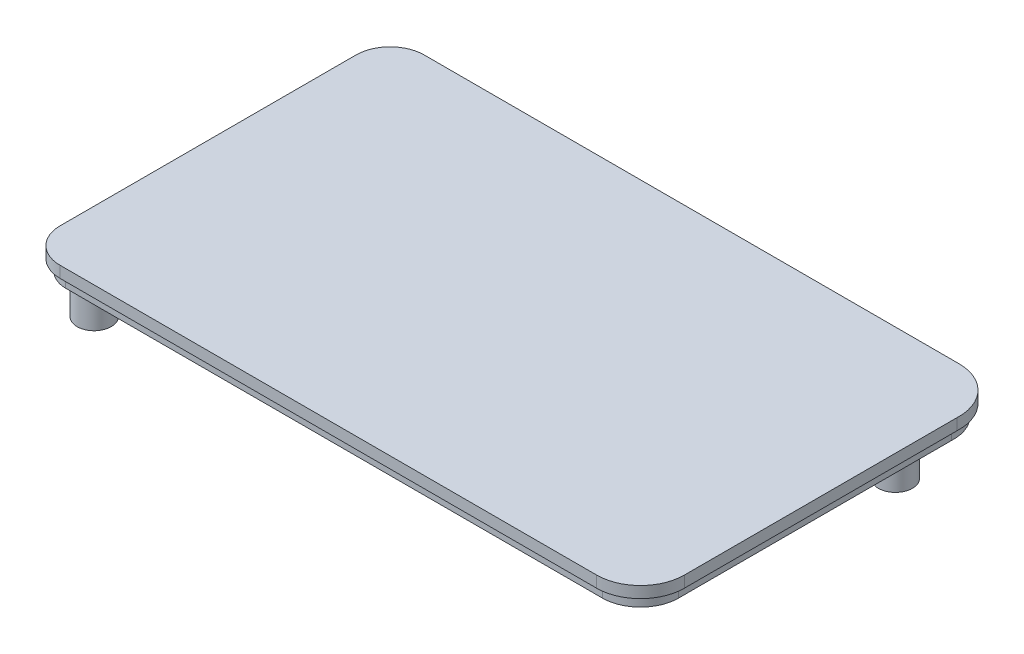
SolidWorks part; units mm, degrees
ref_plane "Front" through (0, 0, 0) normal (0, 0, 1) x (1, 0, 0)
ref_plane "Top" through (0, 0, 0) normal (0, 1, 0) x (1, 0, 0)
ref_plane "Right" through (0, 0, 0) normal (1, 0, 0) x (0, 0, -1)
sketch "Çizim1" plane through (0, 0, 0) normal (0, 1, 0) x (1, 0, 0)
  line L0 (69.3543, 0) -> (22.2059, 0)
  line L9 (19.2052, 3.0007) -> (19.2052, 28.9993)
  line L10 (22.2059, 32) -> (69.2041, 32)
  line L11 (73.204, 27.8016) -> (73.2052, 3.8497)
  arc A0 (19.2052, 28.9993) -> (22.2059, 32) centre (22.2059, 28.9993) cw
  arc A1 (73.204, 27.8016) -> (69.2041, 32) centre (69.2041, 27.9954) ccw
  arc A2 (19.2052, 3.0007) -> (22.2059, 0) centre (22.2059, 3.0007) ccw
  arc A3 (69.3543, 0) -> (73.2052, 3.8497) centre (69.3543, 3.8509) ccw
extrude "Yükseklik-Ekstrüzyon1" add sketch "Çizim1" along normal blind 2
sketch "Çizim2" plane through (0, 0, 0) normal (0, -1, 0) x (1, 0, 0)
  line L0 (22.2059, -0.5) -> (69.3543, -0.5)
  line L1 (72.7052, -3.8498) -> (72.7046, -27.8258)
  line L2 (69.2041, -31.5) -> (22.2059, -31.5)
  line L3 (19.7052, -28.9993) -> (19.7052, -3.0007)
  line L4 (22.2059, 0) -> (69.3543, 0)
  line L5 (73.2052, -3.8498) -> (73.2046, -27.8141)
  line L6 (69.2041, -32) -> (22.2059, -32)
  line L7 (19.2052, -28.9993) -> (19.2052, -3.0007)
  arc A0 (19.7052, -3.0007) -> (22.2059, -0.5) centre (22.2059, -3.0007) cw
  arc A1 (19.7052, -28.9993) -> (22.2059, -31.5) centre (22.2059, -28.9993) ccw
  arc A2 (69.2041, -31.5) -> (72.7046, -27.8258) centre (69.2041, -27.9954) ccw
  arc A3 (72.7052, -3.8498) -> (69.3543, -0.5) centre (69.3543, -3.8509) ccw
  arc A4 (72.7052, -3.8498) -> (69.3543, -0.5) centre (69.3543, -3.8509) ccw construction
  arc A5 (73.2052, -3.8498) -> (69.3543, 0) centre (69.3543, -3.8509) ccw
  arc A6 (69.2041, -32) -> (73.2046, -27.8141) centre (69.2041, -27.9954) ccw
  arc A7 (19.2052, -28.9993) -> (22.2059, -32) centre (22.2059, -28.9993) ccw
  arc A8 (19.2052, -3.0007) -> (22.2059, 0) centre (22.2059, -3.0007) cw
  dimension "D1" = 0.5
extrude "Kes-Ekstrüzyon1" cut sketch "Çizim2" against normal blind 1
sketch "Çizim6" plane through (0, 0, 0) normal (0, -1, 0) x (1, 0, 0)
  circle A0 centre (22.2059, -3.0007) radius 1.001
  circle A1 centre (22.2059, -3.0007) radius 1.501
  circle A2 centre (69.7052, -25.9) radius 1
  circle A3 centre (69.7052, -25.9) radius 1.5
extrude "Yükseklik-Ekstrüzyon3" add sketch "Çizim6" along normal up to surface (3.4254 mm away)
